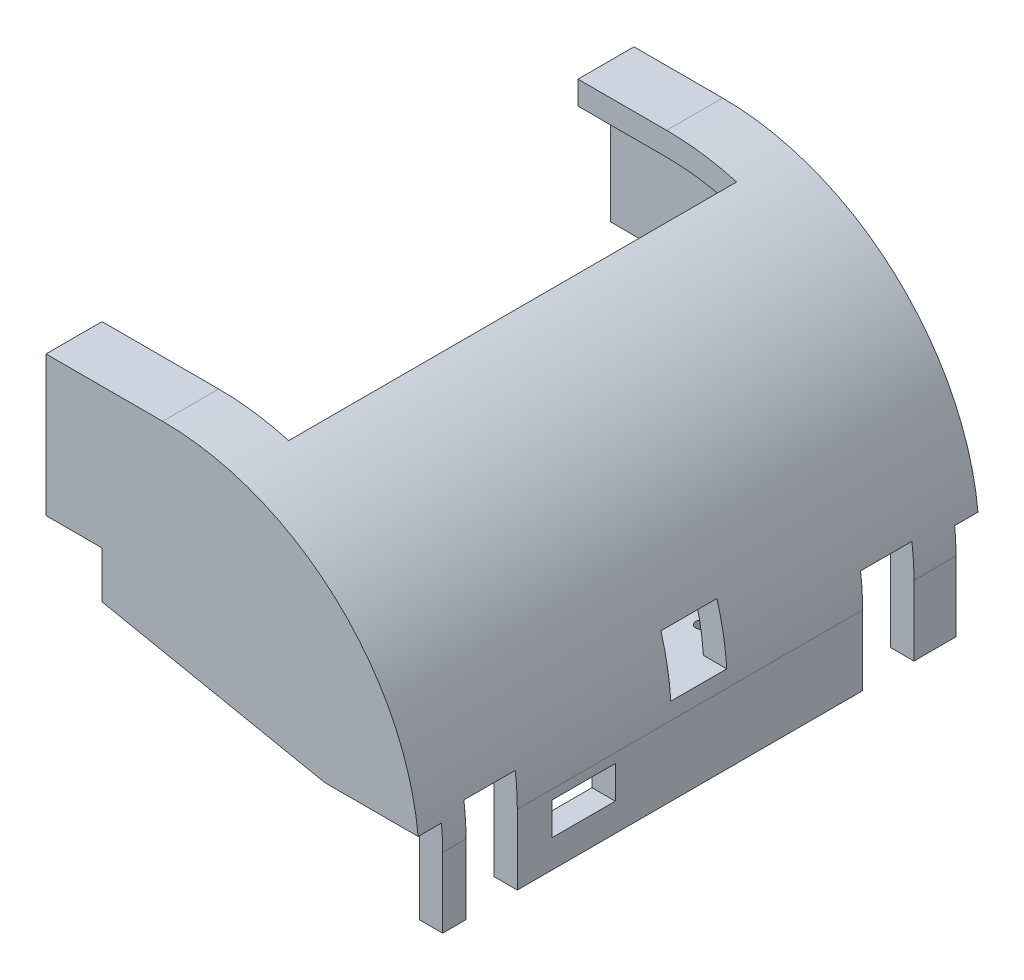
SolidWorks part; units mm, degrees
ref_plane "Front Plane" through (0, 0, 0) normal (0, 0, 1) x (1, 0, 0)
ref_plane "Top Plane" through (0, 0, 0) normal (0, 1, 0) x (1, 0, 0)
ref_plane "Right Plane" through (0, 0, 0) normal (1, 0, 0) x (0, 0, -1)
sketch "Sketch1" plane through (0, 0, 0) normal (0, 0, 1) x (1, 0, 0)
  line L1 (13.568, -0.5417) -> (18.568, -0.5417)
  line L2 (13.568, -0.5417) -> (13.568, 14.4583)
  line L3 (-36.432, 69.4583) -> (-69.432, 69.4583)
  line L4 (18.568, -0.5417) -> (18.568, 14.4583)
  line L5 (-69.432, 69.4583) -> (-69.432, 64.4583)
  line L6 (-69.432, 64.4583) -> (-36.432, 64.4583)
  arc A0 (18.568, 14.4583) -> (-36.432, 69.4583) centre (-36.432, 14.4583) ccw
  arc A1 (13.568, 14.4583) -> (-36.432, 64.4583) centre (-36.432, 14.4583) ccw
  dimension "D1" = 5
  dimension "D2" = 55
  dimension "D3" = 15
  dimension "D4" = 33
extrude "Boss-Extrude1" add sketch "Sketch1" along normal blind 110
sketch "Sketch2" plane through (13.568, 0, 0) normal (-1, 0, 0) x (0, 0, 1)
  line L0 (110, 14.4583) -> (110, -0.5417) construction
  line L1 (40, 17.9583) -> (70, 17.9583)
  line L2 (40, 17.9583) -> (40, 5.4583)
  line L3 (40, 5.4583) -> (70, 5.4583)
  line L4 (70, 17.9583) -> (70, 5.4583)
  line L6 (110, -0.5417) -> (0, -0.5417) construction
  dimension "D1" = 12.5
  dimension "D2" = 30
  dimension "D3" = 40
  dimension "D5" = 6
extrude "Boss-Extrude2" add sketch "Sketch2" along normal blind 35
sketch "Sketch3" plane through (0, 0, 40) normal (0, 0, -1) x (-1, 0, 0)
  line L0 (21.432, 5.4583) -> (-13.568, 5.4583) construction
  line L1 (-13.568, 14.4583) -> (-13.568, 5.4583) construction
  circle A0 centre (3.932, 5.4583) radius 8
  dimension "D1" = 16
  dimension "D2" = 17.5
extrude "Cut-Extrude1" cut sketch "Sketch3" against normal through all
sketch "Sketch4" plane through (0, 5.4583, 0) normal (0, -1, 0) x (1, 0, 0)
  line L0 (-21.432, 40) -> (-21.432, 70) construction
  line L2 (4.068, 70) -> (4.068, 40) construction
  line L3 (-21.432, 40) -> (-11.932, 40) construction
  line L4 (4.068, 40) -> (13.568, 40) construction
  line L5 (4.068, 70) -> (13.568, 70) construction
  line L6 (-21.432, 70) -> (-11.932, 70) construction
  circle A0 centre (-17.932, 43.5) radius 1.5
  circle A1 centre (-17.932, 66.5) radius 1.5
  circle A2 centre (7.568, 43.5) radius 1.25
  circle A3 centre (7.568, 66.5) radius 1.25
  dimension "D1" = 3
  dimension "D2" = 3
  dimension "D3" = 2.5
  dimension "D4" = 2.5
  dimension "D5" = 3.5
  dimension "D7" = 3.5
  dimension "D8" = 3.5
  dimension "D9" = 3.5
  dimension "D10" = 3.5
  dimension "D11" = 3.5
  dimension "D12" = 3.5
  dimension "D6" = 3.5
extrude "Cut-Extrude2" cut sketch "Sketch4" against normal up to surface (12.5 mm away) up to face at (-3.9933, 17.9583, 55)
sketch "Sketch5" plane through (0, 0, 40) normal (0, 0, -1) x (-1, 0, 0)
  line L1 (11.932, 5.4583) -> (21.432, 5.4583)
  line L2 (11.932, 5.4583) -> (11.932, 17.9583)
  line L3 (11.932, 17.9583) -> (21.432, 17.9583)
  line L4 (21.432, 5.4583) -> (21.432, 17.9583)
extrude "Cut-Extrude3" cut sketch "Sketch5" against normal through all
fillet "Fillet4" radius 0.5 1 edges at (-11.932, 5.4583, 55)
sketch "Sketch6" plane through (0, 0, 110) normal (0, 0, 1) x (1, 0, 0)
  line L0 (18.3104, 19.775) -> (-1.6896, 19.775)
  line L1 (-49.432, 29.4583) -> (-1.6896, 19.775)
  line L3 (-69.432, 39.4583) -> (-49.432, 39.4583)
  line L5 (-69.432, 39.4583) -> (-69.432, 69.4583)
  line L6 (-69.432, 69.4583) -> (-36.432, 69.4583)
  line L7 (-49.432, 39.4583) -> (-49.432, 29.4583)
  arc A0 (18.3104, 19.775) -> (-36.432, 69.4583) centre (-36.432, 14.4583) ccw
  arc A1 (13.568, 14.4583) -> (-36.432, 64.4583) centre (-36.432, 14.4583) ccw construction
  arc A2 (18.568, 14.4583) -> (-36.432, 69.4583) centre (-36.432, 14.4583) ccw construction
  dimension "D1" = 33
  dimension "D2" = 0
  dimension "D7" = 0
  dimension "D3" = 20
  dimension "D4" = 10
  dimension "D5" = 30
  dimension "D6" = 20
extrude "Boss-Extrude3" add sketch "Sketch6" along normal blind 5
sketch "Sketch7" plane through (13.568, 0, 0) normal (-1, 0, 0) x (0, 0, 1)
  line L0 (70, 17.9583) -> (40, 17.9583) construction
  line L1 (49, 29.9583) -> (61, 29.9583)
  line L2 (49, 29.9583) -> (49, 17.9583)
  line L3 (49, 17.9583) -> (61, 17.9583)
  line L4 (61, 29.9583) -> (61, 17.9583)
  line L5 (0, 14.4583) -> (0, -0.5417) construction
  line L6 (110, -0.5417) -> (0, -0.5417) construction
  line L7 (105, -0.5417) -> (94, -0.5417)
  line L8 (105, -0.5417) -> (105, 21.4583)
  line L9 (105, 21.4583) -> (94, 21.4583)
  line L10 (94, -0.5417) -> (94, 21.4583)
  line L11 (110, 14.4583) -> (110, -0.5417) construction
  line L13 (20, -0.5417) -> (20, 21.4583)
  line L14 (9, 21.4583) -> (20, 21.4583)
  line L15 (9, -0.5417) -> (9, 21.4583)
  line L16 (9, -0.5417) -> (20, -0.5417)
  line L17 (73, 5.4583) -> (86.6, 5.4583)
  line L18 (73, 5.4583) -> (73, 12.4583)
  line L19 (73, 12.4583) -> (86.6, 12.4583)
  line L20 (86.6, 5.4583) -> (86.6, 12.4583)
  line L21 (73, 5.4583) -> (86.6, 12.4583) construction
  line L22 (73, 12.4583) -> (86.6, 5.4583) construction
  line L23 (70, 5.4583) -> (70, 14.4583) construction
  point P16 (79.8, 8.9583)
  dimension "D1" = 12
  dimension "D2" = 12
  dimension "D3" = 49
  dimension "D4" = 5
  dimension "D5" = 11
  dimension "D6" = 22
  dimension "D7" = 0
  dimension "D8" = 13.6
  dimension "D9" = 7
  dimension "D10" = 13
  dimension "D11" = 3
  dimension "D12" = 22
extrude "Cut-Extrude4" cut sketch "Sketch7" against normal through all both and the other way through all
sketch "Sketch8" plane through (0, 0, 0) normal (0, 0, -1) x (-1, 0, 0)
  line L0 (36.432, 69.4583) -> (69.432, 69.4583)
  line L1 (69.432, 69.4583) -> (69.432, 64.4583)
  line L2 (69.432, 64.4583) -> (69.432, 39.4583)
  line L3 (49.432, 29.4583) -> (1.7077, 19.9583)
  line L4 (69.432, 39.4583) -> (49.432, 39.4583)
  line L5 (49.432, 39.4583) -> (49.432, 29.4583)
  line L6 (1.7077, 19.9583) -> (-18.2923, 19.9583)
  arc A0 (36.432, 69.4583) -> (-18.2923, 19.9583) centre (36.432, 14.4583) ccw
  dimension "D1" = 25
  dimension "D2" = 20
  dimension "D3" = 10
  dimension "D4" = 20
extrude "Boss-Extrude4" add sketch "Sketch8" along normal blind 5
sketch "Sketch9" plane through (0, 69.4583, 0) normal (0, 1, 0) x (1, 0, 0)
  line L0 (-69.432, -115) -> (-69.432, 5) construction
  line L1 (-55.432, -7) -> (-21.432, -7)
  line L2 (-92.4251, -7) -> (-92.4251, -103)
  line L3 (-61.432, -103) -> (-21.432, -103)
  line L4 (-21.432, -7) -> (-21.432, -103)
  line L5 (-36.432, -115) -> (-69.432, -115) construction
  line L6 (-55.432, -7) -> (-55.432, 8.2141)
  line L7 (-55.432, 8.2141) -> (-92.4251, 8.2141)
  line L8 (-92.4251, 8.2141) -> (-92.4251, -7)
  line L9 (-61.432, -103) -> (-61.432, -133.7159)
  line L10 (-61.432, -133.7159) -> (-92.4251, -133.7159)
  line L11 (-92.4251, -133.7159) -> (-92.4251, -103)
  line L12 (-69.432, -115) -> (-69.432, 5) construction
  dimension "D1" = 48
  dimension "D2" = 96
  dimension "D3" = 12
  dimension "D4" = 14
  dimension "D5" = 8
  dimension "D6" = 96
extrude "Cut-Extrude5" cut sketch "Sketch9" against normal through all
